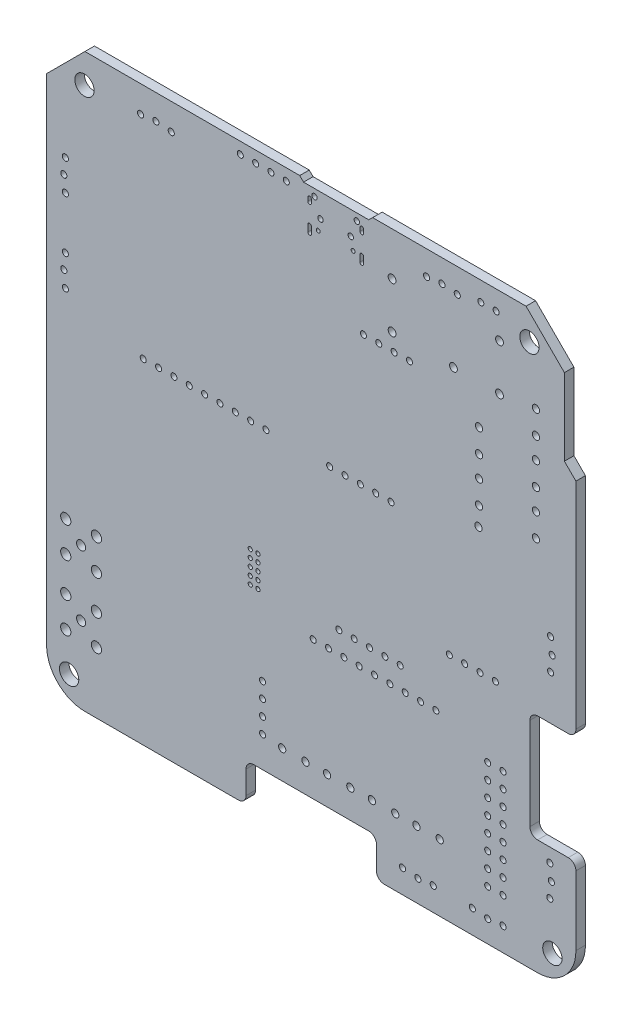
SolidWorks part; units mm, degrees
ref_plane "Front" through (0, 0, 0) normal (0, 0, 1) x (1, 0, 0)
ref_plane "Top" through (0, 0, 0) normal (0, 1, 0) x (1, 0, 0)
ref_plane "Right" through (0, 0, 0) normal (1, 0, 0) x (0, 0, -1)
ref_plane "Plane1" through (0, 0, 1.5748) normal (0, 0, 1) x (1, 0, 0)
sketch "Sketch1" plane through (0, 0, 1.5748) normal (0, 0, 1) x (1, 0, 0)
  line L0 (8.0666, 44.2757) -> (8.0666, 44.8757)
  line L1 (8.6666, 44.8757) -> (8.6666, 44.2757)
  line L2 (8.0666, 39.8757) -> (8.0666, 40.9757)
  line L3 (8.6666, 40.9757) -> (8.6666, 39.8757)
  line L4 (-0.5734, 39.8757) -> (-0.5734, 40.9757)
  line L5 (0.0266, 40.9757) -> (0.0266, 39.8757)
  line L6 (-0.5734, 44.2757) -> (-0.5734, 44.8757)
  line L7 (0.0266, 44.8757) -> (0.0266, 44.2757)
  line L8 (-37.465, -47.3075) -> (-12.065, -47.3075)
  line L9 (-10.795, -46.0375) -> (-10.795, -42.2275)
  line L10 (-9.525, -40.9575) -> (9.525, -40.9575)
  line L11 (10.795, -42.2275) -> (10.795, -46.0375)
  line L12 (12.065, -47.3075) -> (37.465, -47.3075)
  line L13 (43.815, -40.9575) -> (43.815, -29.5275)
  line L14 (42.545, -28.2575) -> (37.465, -28.2575)
  line L15 (36.195, -26.9875) -> (36.195, -11.7475)
  line L16 (37.465, -10.4775) -> (42.545, -10.4775)
  line L17 (43.815, -9.2075) -> (43.815, 26.3525)
  line L18 (43.815, 26.3525) -> (41.91, 28.2575)
  line L19 (41.91, 28.2575) -> (41.91, 40.9575)
  line L20 (41.91, 40.9575) -> (35.56, 47.3075)
  line L21 (35.56, 47.3075) -> (10.16, 47.3075)
  line L22 (10.16, 47.3075) -> (9.525, 46.6725)
  line L23 (9.525, 46.6725) -> (-1.27, 46.6725)
  line L24 (-1.27, 46.6725) -> (-1.905, 47.3075)
  line L25 (-1.905, 47.3075) -> (-37.465, 47.3075)
  line L26 (-37.465, 47.3075) -> (-43.815, 40.9575)
  line L27 (-43.815, 40.9575) -> (-43.815, -40.9575)
  circle A0 centre (39.497, -35.6235) radius 0.508
  circle A1 centre (39.9161, -43.2816) radius 1.6
  circle A2 centre (39.751, -33.0835) radius 0.508
  circle A3 centre (39.497, -30.5435) radius 0.508
  circle A4 centre (39.624, -3.1115) radius 0.508
  circle A5 centre (39.878, -0.5715) radius 0.508
  circle A6 centre (39.624, 1.9685) radius 0.508
  circle A7 centre (-40.0839, -43.2816) radius 1.6
  circle A8 centre (15.113, -43.434) radius 0.508
  circle A9 centre (20.193, -43.434) radius 0.508
  circle A10 centre (17.653, -43.688) radius 0.508
  circle A11 centre (26.67, -43.434) radius 0.508
  circle A12 centre (29.21, -39.0525) radius 0.5
  circle A13 centre (31.75, -39.0525) radius 0.5
  circle A14 centre (31.75, -43.434) radius 0.508
  circle A15 centre (29.21, -43.688) radius 0.508
  circle A16 centre (-37.5439, 42.4434) radius 1.6
  circle A17 centre (-28.2575, 42.926) radius 0.508
  circle A18 centre (-11.7475, 45.4025) radius 0.5
  circle A19 centre (-23.1775, 42.926) radius 0.508
  circle A20 centre (-25.7175, 43.18) radius 0.508
  circle A21 centre (36.1161, 42.4434) radius 1.6
  circle A22 centre (31.1623, 40.1474) radius 0.6477
  circle A23 centre (30.607, 44.1325) radius 0.5
  circle A24 centre (28.067, 44.1325) radius 0.5
  circle A25 centre (31.1623, 32.5274) radius 0.6477
  circle A26 centre (37.1981, 33.4074) radius 0.6
  circle A27 centre (-9.2075, 45.4025) radius 0.5
  circle A28 centre (19.0941, 43.3014) radius 0.508
  circle A29 centre (24.1741, 43.3014) radius 0.508
  circle A30 centre (21.6341, 43.5554) radius 0.508
  circle A31 centre (23.5423, 32.5274) radius 0.6477
  circle A32 centre (6.5386, 42.8041) radius 0.45
  circle A33 centre (7.5386, 45.5041) radius 0.4445
  arc A34 (8.6666, 44.2757) -> (8.0666, 44.2757) centre (8.3666, 44.2757) cw
  arc A35 (8.0666, 44.8757) -> (8.6666, 44.8757) centre (8.3666, 44.8757) cw
  circle A36 centre (13.3823, 40.1474) radius 0.6477
  arc A37 (8.6666, 39.8757) -> (8.0666, 39.8757) centre (8.3666, 39.8757) cw
  arc A38 (8.0666, 40.9757) -> (8.6666, 40.9757) centre (8.3666, 40.9757) cw
  circle A39 centre (6.9366, 40.9257) radius 0.325
  circle A40 centre (13.3823, 32.5274) radius 0.6477
  circle A41 centre (1.1566, 40.9257) radius 0.325
  arc A42 (0.0266, 39.8757) -> (-0.5734, 39.8757) centre (-0.2734, 39.8757) cw
  arc A43 (-0.5734, 40.9757) -> (0.0266, 40.9757) centre (-0.2734, 40.9757) cw
  circle A44 centre (0.5386, 45.5041) radius 0.4445
  circle A45 centre (1.5386, 42.8041) radius 0.45
  circle A46 centre (-4.1275, 45.4025) radius 0.5
  circle A47 centre (-6.6675, 45.4025) radius 0.5
  arc A48 (0.0266, 44.2757) -> (-0.5734, 44.2757) centre (-0.2734, 44.2757) cw
  arc A49 (-0.5734, 44.8757) -> (0.0266, 44.8757) centre (-0.2734, 44.8757) cw
  circle A50 centre (-40.64, -32.0675) radius 0.85
  circle A51 centre (-38.1, -34.6075) radius 0.75
  circle A52 centre (-40.64, -37.1475) radius 0.85
  circle A53 centre (31.75, -28.8925) radius 0.5
  circle A54 centre (-8.0645, -28.2575) radius 0.5
  circle A55 centre (29.21, -28.8925) radius 0.5
  circle A56 centre (31.75, -36.5125) radius 0.5
  circle A57 centre (-8.0645, -33.3375) radius 0.5
  circle A58 centre (31.75, -33.9725) radius 0.5
  circle A59 centre (-8.0645, -30.7975) radius 0.5
  circle A60 centre (29.21, -31.4325) radius 0.5
  circle A61 centre (31.75, -31.4325) radius 0.5
  circle A62 centre (-35.56, -32.0675) radius 0.85
  circle A63 centre (-35.56, -37.1475) radius 0.85
  circle A64 centre (13.9013, -36.2585) radius 0.6
  circle A65 centre (21.2673, -36.2585) radius 0.6
  circle A66 centre (17.4117, -36.2585) radius 0.6
  circle A67 centre (29.21, -36.5125) radius 0.5
  circle A68 centre (29.21, -33.9725) radius 0.5
  circle A69 centre (6.4718, -36.2585) radius 0.6
  circle A70 centre (10.0457, -36.2585) radius 0.6
  circle A71 centre (-0.9577, -36.2585) radius 0.6
  circle A72 centre (2.6162, -36.2585) radius 0.6
  circle A73 centre (-4.8133, -36.2585) radius 0.6
  circle A74 centre (-8.0645, -35.8775) radius 0.5
  circle A75 centre (37.1981, 29.5518) radius 0.6
  circle A76 centre (30.48, -9.017) radius 0.5
  circle A77 centre (31.75, -21.2725) radius 0.5
  circle A78 centre (31.75, -23.8125) radius 0.5
  circle A79 centre (31.75, -26.3525) radius 0.5
  circle A80 centre (37.1981, 18.6962) radius 0.6
  circle A81 centre (37.1981, 14.8406) radius 0.6
  circle A82 centre (37.1981, 26.0518) radius 0.6
  circle A83 centre (37.1981, 22.1962) radius 0.6
  circle A84 centre (13.716, 29.7815) radius 0.5
  circle A85 centre (16.256, 29.7815) radius 0.5
  circle A86 centre (-40.7035, 30.48) radius 0.508
  circle A87 centre (-40.9575, 27.94) radius 0.508
  circle A88 centre (8.636, 29.7815) radius 0.5
  circle A89 centre (11.176, 29.7815) radius 0.5
  circle A90 centre (-40.7035, 25.4) radius 0.508
  circle A91 centre (-40.9575, 14.2875) radius 0.508
  circle A92 centre (-40.7035, 16.8275) radius 0.508
  circle A93 centre (-40.7035, 11.7475) radius 0.508
  circle A94 centre (3.048, 8.0645) radius 0.5
  circle A95 centre (2.8575, -18.0975) radius 0.5
  circle A96 centre (0.3175, -18.0975) radius 0.5
  circle A97 centre (4.572, -14.5923) radius 0.5
  circle A98 centre (-38.1, -23.8125) radius 0.75
  circle A99 centre (-40.64, -26.3525) radius 0.85
  circle A100 centre (-35.56, -26.3525) radius 0.85
  circle A101 centre (-8.8265, -15.4305) radius 0.35
  circle A102 centre (-10.0965, -15.4305) radius 0.35
  circle A103 centre (-10.0965, -10.3505) radius 0.35
  circle A104 centre (-10.0965, -11.6205) radius 0.35
  circle A105 centre (-8.8265, -11.6205) radius 0.35
  circle A106 centre (-8.8265, -10.3505) radius 0.35
  circle A107 centre (-10.0965, -12.8905) radius 0.35
  circle A108 centre (-8.8265, -12.8905) radius 0.35
  circle A109 centre (-8.8265, -14.1605) radius 0.35
  circle A110 centre (-10.0965, -14.1605) radius 0.35
  circle A111 centre (-12.573, 8.0645) radius 0.5
  circle A112 centre (-15.113, 8.0645) radius 0.5
  circle A113 centre (-10.033, 8.0645) radius 0.5
  circle A114 centre (-7.493, 8.0645) radius 0.5
  circle A115 centre (-27.813, 8.0645) radius 0.5
  circle A116 centre (-22.733, 8.0645) radius 0.5
  circle A117 centre (-25.273, 8.0645) radius 0.5
  circle A118 centre (-20.193, 8.0645) radius 0.5
  circle A119 centre (-17.653, 8.0645) radius 0.5
  circle A120 centre (-35.56, -21.2725) radius 0.85
  circle A121 centre (-40.64, -21.2725) radius 0.85
  circle A122 centre (7.9375, -18.0975) radius 0.5
  circle A123 centre (10.4775, -18.0975) radius 0.5
  circle A124 centre (5.3975, -18.0975) radius 0.5
  circle A125 centre (7.112, -14.5923) radius 0.5
  circle A126 centre (9.652, -14.5923) radius 0.5
  circle A127 centre (8.128, 8.0645) radius 0.5
  circle A128 centre (5.588, 8.0645) radius 0.5
  circle A129 centre (10.668, 8.0645) radius 0.5
  circle A130 centre (22.86, -9.017) radius 0.5
  circle A131 centre (25.4, -9.017) radius 0.5
  circle A132 centre (18.0975, -18.0975) radius 0.5
  circle A133 centre (20.6375, -18.0975) radius 0.5
  circle A134 centre (15.5575, -18.0975) radius 0.5
  circle A135 centre (14.732, -14.5923) radius 0.5
  circle A136 centre (12.192, -14.5923) radius 0.5
  circle A137 centre (13.0175, -18.0975) radius 0.5
  circle A138 centre (13.208, 8.0645) radius 0.5
  circle A139 centre (27.94, -9.017) radius 0.5
  circle A140 centre (29.21, -21.2725) radius 0.5
  circle A141 centre (29.21, -23.8125) radius 0.5
  circle A142 centre (29.21, -26.3525) radius 0.5
  circle A143 centre (27.7721, 18.6962) radius 0.6
  circle A144 centre (27.7721, 14.8406) radius 0.6
  circle A145 centre (27.6821, 11.7485) radius 0.6
  circle A146 centre (27.7721, 22.1962) radius 0.6
  circle A147 centre (27.7721, 26.0518) radius 0.6
  arc A148 (-43.815, -40.9575) -> (-37.465, -47.3075) centre (-37.465, -40.9575) ccw
  arc A149 (-12.065, -47.3075) -> (-10.795, -46.0375) centre (-12.065, -46.0375) ccw
  arc A150 (-10.795, -42.2275) -> (-9.525, -40.9575) centre (-9.525, -42.2275) cw
  arc A151 (9.525, -40.9575) -> (10.795, -42.2275) centre (9.525, -42.2275) cw
  arc A152 (10.795, -46.0375) -> (12.065, -47.3075) centre (12.065, -46.0375) ccw
  arc A153 (37.465, -47.3075) -> (43.815, -40.9575) centre (37.465, -40.9575) ccw
  arc A154 (43.815, -29.5275) -> (42.545, -28.2575) centre (42.545, -29.5275) ccw
  arc A155 (37.465, -28.2575) -> (36.195, -26.9875) centre (37.465, -26.9875) cw
  arc A156 (36.195, -11.7475) -> (37.465, -10.4775) centre (37.465, -11.7475) cw
  arc A157 (42.545, -10.4775) -> (43.815, -9.2075) centre (42.545, -9.2075) ccw
extrude "Boss-Extrude1" add sketch "Sketch1" against normal blind 1.5748
